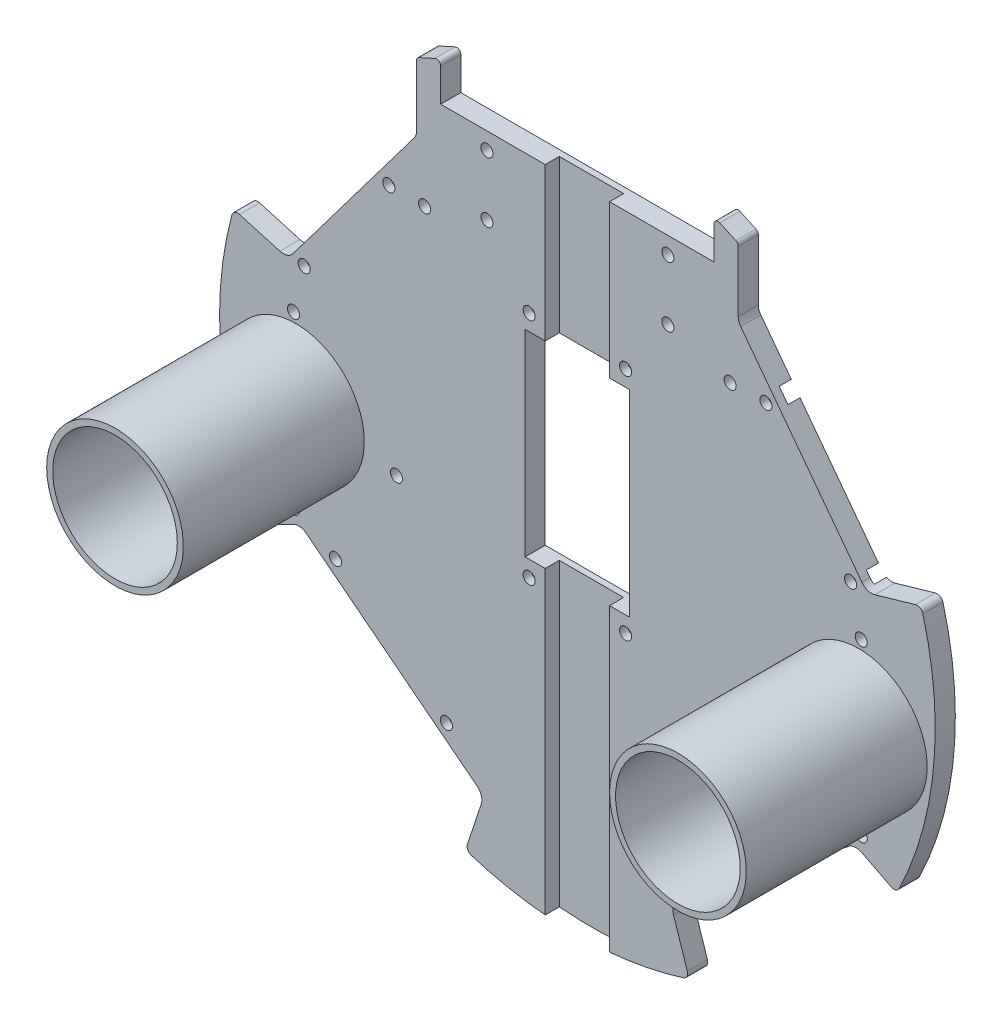
SolidWorks part; units mm, degrees
ref_plane "前视基准面" through (0, 0, 0) normal (0, 0, 1) x (1, 0, 0)
ref_plane "上视基准面" through (0, 0, 0) normal (0, 1, 0) x (1, 0, 0)
ref_plane "右视基准面" through (0, 0, 0) normal (1, 0, 0) x (0, 0, -1)
other "Configuration Table"
sketch "草图1" plane through (0, 0, 0) normal (0, 0, 1) x (1, 0, 0)
  line L0 (0, 70) -> (0, -70) construction
  line L1 (-70, 0) -> (70, 0) construction
  line L2 (40.6041, 62.4314) -> (55.9045, 42.1271)
  line L3 (55.9045, 42.1271) -> (0, 0) construction
  line L4 (55.9045, 42.1271) -> (70.756, 22.4184)
  line L6 (-34, 77) -> (34, 77)
  line L7 (22.5, 65) -> (-22.5, 65) construction
  line L8 (22.5, 65) -> (22.5, 50) construction
  line L9 (22.5, 50) -> (-22.5, 50) construction
  line L10 (-22.5, 65) -> (-22.5, 50) construction
  line L11 (0, 77) -> (0, 70) construction
  line L20 (0, 0) -> (43.0963, -55.1608) construction
  line L22 (43.0963, -55.1608) -> (24.9165, -69.3644)
  line L23 (43.0963, -55.1608) -> (67.4566, -36.1284)
  line L24 (23.9138, -72.6662) -> (27.8213, -84.5398)
  line L25 (70.6599, -35.8166) -> (79.3841, -40.2388)
  line L26 (40, 74) -> (40, 64.2368)
  line L27 (-70.6599, -35.8166) -> (-79.3841, -40.2388)
  line L28 (-43.0963, -55.1608) -> (-67.4566, -36.1284)
  line L29 (-43.0963, -55.1608) -> (-24.9165, -69.3644)
  line L30 (-23.9138, -72.6662) -> (-27.8213, -84.5398)
  line L31 (73.9834, 21.3414) -> (85.5133, 24.6673)
  line L32 (-55.9045, 42.1271) -> (-70.756, 22.4184)
  line L33 (-73.9834, 21.3414) -> (-85.5133, 24.6673)
  line L34 (40, 74) -> (40, 80.064)
  line L35 (34, 77) -> (34, 82.7904)
  line L36 (40, 80.064) -> (34, 82.7904)
  line L37 (-40.6041, 62.4314) -> (-55.9045, 42.1271)
  line L38 (-40, 74) -> (-40, 64.2368)
  line L39 (-40, 74) -> (-40, 80.064)
  line L40 (-40, 80.064) -> (-34, 82.7904)
  line L41 (-34, 77) -> (-34, 82.7904)
  arc A0 (-85.5133, 24.6673) -> (-79.3841, -40.2388) centre (0, 0) ccw
  circle A1 centre (0, 0) radius 70 construction
  circle A5 centre (67.9521, 21.1544) radius 1.5 construction
  circle A6 centre (46.8886, 49.1066) radius 1.5 construction
  circle A17 centre (-67.9521, 21.1544) radius 1.5 construction
  arc A18 (40.6041, 62.4314) -> (40, 64.2368) centre (43, 64.2368) cw
  circle A19 centre (-46.8886, 49.1066) radius 1.5 construction
  circle A21 centre (32.5812, -59.569) radius 1.5 construction
  circle A22 centre (60.1616, -38.0208) radius 1.5 construction
  arc A23 (23.9138, -72.6662) -> (24.9165, -69.3644) centre (26.7635, -71.7284) cw
  arc A24 (70.6599, -35.8166) -> (67.4566, -36.1284) centre (69.3035, -38.4925) ccw
  arc A25 (79.3841, -40.2388) -> (85.5133, 24.6673) centre (0, 0) ccw
  circle A26 centre (-32.5812, -59.569) radius 1.5 construction
  circle A27 centre (-60.1616, -38.0208) radius 1.5 construction
  arc A28 (-70.6599, -35.8166) -> (-67.4566, -36.1284) centre (-69.3035, -38.4925) cw
  arc A29 (-23.9138, -72.6662) -> (-24.9165, -69.3644) centre (-26.7635, -71.7284) ccw
  arc A30 (-27.8213, -84.5398) -> (27.8213, -84.5398) centre (0, 0) ccw
  arc A31 (73.9834, 21.3414) -> (70.756, 22.4184) centre (73.1519, 24.2238) cw
  arc A32 (-73.9834, 21.3414) -> (-70.756, 22.4184) centre (-73.1519, 24.2238) ccw
  circle A33 centre (0, 0) radius 89.5 construction
  arc A34 (-40.6041, 62.4314) -> (-40, 64.2368) centre (-43, 64.2368) ccw
  point P10 (55.9045, 42.1271)
  point P16 (70.581, 24.7855)
  point P21 (0, 65)
  point P33 (40, 63.233)
  point P38 (40, 77)
  point P43 (-40, 63.233)
  point P55 (40, -63.233)
  point P60 (23.2545, -70.6629)
  point P64 (68.9591, -34.9545)
  dimension "D1" = 178
  dimension "D2" = 140
  dimension "D7" = 3
  dimension "D14" = 24
  dimension "D3" = 40
  dimension "D4" = 3
  dimension "D15" = 3
  dimension "D17" = 3
  dimension "D21" = 11
  dimension "D5" = 6
  dimension "D23" = 3
  dimension "D26" = 3
  dimension "D29" = 3
  dimension "D30" = 3
  dimension "D31" = 179
  dimension "D32" = 77
  dimension "D6" = 3
  dimension "D8" = 53
  dimension "D9" = 45
  dimension "D10" = 15
  dimension "D11" = 22.5
  dimension "D12" = 12
  dimension "D13" = 12
  dimension "D16" = 3
  dimension "D18" = 90
  dimension "D19" = 11
  dimension "D20" = 38
  dimension "D22" = 3
  dimension "D24" = 3
  dimension "D25" = 24
  dimension "D27" = 58
  dimension "D28" = 12.5
  dimension "D33" = 6
extrude "整车底板外形拉伸" add sketch "草图1" along normal blind 5
fillet "圆角3" radius 1.5 1 edges at (79.3841, -40.2388, 2.5)
fillet "圆角4" radius 1.5 1 edges at (27.8213, -84.5398, 2.5)
fillet "圆角5" radius 1.5 1 edges at (-27.8213, -84.5398, 2.5)
fillet "圆角6" radius 1.5 1 edges at (-79.3841, -40.2388, 2.5)
fillet "圆角8" radius 1.5 1 edges at (85.5133, 24.6673, 2.5)
fillet "圆角9" radius 1.5 1 edges at (-85.5133, 24.6673, 2.5)
fillet "圆角10" radius 1 4 edges at (-40, 80.064, 2.5) (40, 80.064, 2.5) (-34, 82.7904, 2.5) (34, 82.7904, 2.5)
sketch "草图3" plane through (0, 0, 5) normal (0, 0, 1) x (1, 0, 0)
  circle A0 centre (70, -9.25) radius 17
  dimension "D1" = 34
  dimension "D2" = 9.25
  dimension "D3" = 70
extrude "电容座" add sketch "草图3" along normal blind 45
sketch "草图4" plane through (0, 0, 50) normal (0, 0, 1) x (1, 0, 0)
  circle A0 centre (70, -9.25) radius 15.5
  dimension "D1" = 31
extrude "电容座内部" cut sketch "草图4" against normal blind 45
mirror "镜向1" about plane through (0, 0, 0) normal (1, 0, 0) of "电容座"
mirror "镜向2" about plane through (0, 0, 0) normal (1, 0, 0) of "电容座内部"
sketch "草图5" plane through (0, 0, 5) normal (0, 0, 1) x (1, 0, 0)
  line L0 (70.756, 22.4184) -> (40.6041, 62.4314) construction
  line L1 (0, 0) -> (55.9045, 42.1271) construction
  line L2 (0, 77) -> (0, 0) construction
  line L3 (34, 77) -> (-34, 77) construction
  line L4 (0, 0) -> (43.0963, -55.1608) construction
  line L5 (24.9165, -69.3644) -> (67.4566, -36.1284) construction
  circle A0 centre (46.8886, 49.1066) radius 1.5
  circle A1 centre (67.9521, 21.1544) radius 1.5
  circle A2 centre (-67.9521, 21.1544) radius 1.5
  circle A3 centre (-46.8886, 49.1066) radius 1.5
  circle A4 centre (60.1616, -38.0208) radius 1.5
  circle A5 centre (32.5812, -59.569) radius 1.5
  circle A6 centre (-60.1616, -38.0208) radius 1.5
  circle A7 centre (-32.5812, -59.569) radius 1.5
  dimension "D1" = 3
  dimension "D5" = 24
  dimension "D7" = 3
  dimension "D9" = 3
  dimension "D12" = 3
  dimension "D2" = 3
  dimension "D3" = 11
  dimension "D4" = 53
  dimension "D6" = 3
  dimension "D8" = 142
  dimension "D10" = 24
  dimension "D11" = 3
  dimension "D13" = 11
  dimension "D14" = 3
extrude "电机安装孔上部分" cut sketch "草图5" against normal blind 2
sketch "草图12" plane through (0, 0, 0) normal (0, 0, -1) x (-1, 0, 0)
  line L0 (0, 0) -> (55.9045, 42.1271) construction
  line L1 (40.6041, 62.4314) -> (70.756, 22.4184) construction
  line L2 (0, 0) -> (0, 77) construction
  line L3 (-34, 77) -> (34, 77) construction
  line L4 (0, 0) -> (43.0963, -55.1608) construction
  line L5 (67.4566, -36.1284) -> (24.9165, -69.3644) construction
  circle A0 centre (46.8886, 49.1066) radius 3.5
  circle A1 centre (68.554, 20.3557) radius 3.5
  circle A2 centre (-68.554, 20.3557) radius 3.5
  circle A3 centre (-46.8886, 49.1066) radius 3.5
  circle A4 centre (32.5812, -59.569) radius 3.5
  circle A5 centre (60.1616, -38.0208) radius 3.5
  circle A6 centre (13.527, -115.9287) radius 3.5
  circle A7 centre (-60.1616, -38.0208) radius 3.5
  circle A8 centre (-32.5812, -59.569) radius 3.5
  dimension "D1" = 7
  dimension "D5" = 7
  dimension "D11" = 7
  dimension "D12" = 7
  dimension "D2" = 11
  dimension "D3" = 3
  dimension "D4" = 25
  dimension "D6" = 3
  dimension "D7" = 11
  dimension "D8" = 24
  dimension "D9" = 3
  dimension "D10" = 3
extrude "电机安装孔下部分" cut sketch "草图12" against normal blind 3
sketch "草图7" plane through (0, 0, 5) normal (0, 0, 1) x (1, 0, 0)
  line L0 (-8, 77) -> (-8, -88.6397)
  line L1 (34, 77) -> (-34, 77) construction
  line L2 (-8, 77) -> (8, 77)
  line L4 (0, 0) -> (0, -22.89) construction
  line L5 (8, 77) -> (8, -88.6397)
  arc A1 (-26.3679, -85.0043) -> (26.3679, -85.0043) centre (0, 0) ccw construction
  arc A3 (-8, -88.6397) -> (8, -88.6397) centre (0, 0) ccw
  point P6 (0, -56)
  point P10 (0, 77)
  dimension "D1" = 16
extrude "挑球铲的槽" cut sketch "草图7" against normal blind 3.5
sketch "草图8" plane through (0, 0, 5) normal (0, 0, 1) x (1, 0, 0)
  line L0 (0, 77) -> (0, -5.3656) construction
  line L1 (8, 77) -> (-8, 77) construction
  line L2 (13, 35) -> (-13, 35)
  line L3 (-13, 35) -> (-13, -14)
  line L4 (-13, -14) -> (13, -14)
  line L5 (0, -5.3656) -> (0, -14) construction
  line L6 (-8, 77) -> (-34, 77) construction
  line L7 (13, 35) -> (13, -14)
  point P13 (0, 35)
  dimension "D1" = 49
  dimension "D2" = 13
  dimension "D3" = 42
extrude "安装电磁铁的槽" cut sketch "草图8" against normal blind 5
sketch "草图9" plane through (0, 0, 5) normal (0, 0, 1) x (1, 0, 0)
  line L0 (8, 35) -> (8, 77) construction
  line L1 (13, 35) -> (8, 35) construction
  line L2 (0, 0) -> (0, 32.0784) construction
  line L3 (-13, 10.5) -> (13, 10.5) construction
  line L4 (-13, 35) -> (-13, -14) construction
  line L5 (13, -14) -> (13, 35) construction
  circle A0 centre (12, 39) radius 1.5
  circle A1 centre (-12, 39) radius 1.5
  circle A2 centre (-12, -18) radius 1.5
  circle A3 centre (12, -18) radius 1.5
  dimension "D2" = 3
  dimension "D1" = 4
  dimension "D3" = 4
extrude "安装电磁铁的孔的上半部分" cut sketch "草图9" against normal blind 2
sketch "草图10" plane through (0, 0, 0) normal (0, 0, -1) x (-1, 0, 0)
  line L0 (8, 35) -> (8, 53.2712) construction
  line L1 (-13, 35) -> (13, 35) construction
  line L2 (0, 35) -> (0, 53.2712) construction
  line L3 (-13, 10.5) -> (13, 10.5) construction
  line L4 (-13, -14) -> (-13, 35) construction
  line L5 (13, 35) -> (13, -14) construction
  circle A0 centre (12, 39) radius 3.5
  circle A1 centre (-12, 39) radius 3.5
  circle A2 centre (12, -18) radius 3.5
  circle A3 centre (-12, -18) radius 3.5
  dimension "D4" = 7
  dimension "D1" = 8
  dimension "D2" = 4
  dimension "D3" = 4
extrude "安装电磁铁的孔下半部分" cut sketch "草图10" against normal blind 3
sketch "草图11" plane through (0, 0, 5) normal (0, 0, 1) x (1, 0, 0)
  line L0 (34, 77) -> (8, 77) construction
  line L1 (22.5, 68.8) -> (22.5, 53.8) construction
  line L2 (0, 77) -> (0, 50.9825) construction
  line L3 (8, 77) -> (-8, 77) construction
  circle A0 centre (22.5, 68.8) radius 1.5
  circle A1 centre (22.5, 53.8) radius 1.5
  circle A2 centre (-22.5, 53.8) radius 1.5
  circle A3 centre (-22.5, 68.8) radius 1.5
  dimension "D1" = 3
  dimension "D5" = 3
  dimension "D2" = 8.2
  dimension "D3" = 15
  dimension "D4" = 45
extrude "嘴部安装孔" cut sketch "草图11" against normal blind 5
sketch "草图14" plane through (0, 0, 0) normal (0, 0, -1) x (-1, 0, 0)
  line L0 (34, 77) -> (34, 73)
  line L1 (-34, 77) -> (-34, 73)
  line L2 (-34, 73) -> (34, 73)
  line L3 (-34, 77) -> (34, 77)
extrude "切除-拉伸1" cut sketch "草图14" against normal blind 10
sketch "草图15" plane through (0, 0, 5) normal (0, 0, 1) x (1, 0, 0)
  line L0 (0, 73) -> (0, 23.218) construction
  line L1 (-8, 73) -> (8, 73) construction
  line L2 (-34, 73) -> (-8, 73) construction
  circle A2 centre (-45, -12.5) radius 1.5
  circle A3 centre (-38, 49) radius 1.5
  circle A4 centre (38, 49) radius 1.5
  circle A5 centre (45, -12.5) radius 1.5
  dimension "D1" = 3
  dimension "D2" = 76
  dimension "D3" = 24
  dimension "D5" = 3
  dimension "D4" = 61.5
  dimension "D6" = 90
extrude "电池盒安装孔" cut sketch "草图15" against normal through all
sketch "草图16" plane through (0, 0, 5) normal (0, 0, 1) x (1, 0, 0)
  line L13 (-70.6, 10) -> (70.6, 10) construction
  line L14 (-70.6, 10) -> (-70.6, -32.2) construction
  line L15 (-70.6, -32.2) -> (70.6, -32.2) construction
  line L16 (70.6, 10) -> (70.6, -32.2) construction
  line L17 (-8, 73) -> (8, 73) construction
  circle A0 centre (-70.6, -32.2) radius 1.5
  circle A1 centre (-70.6, 10) radius 1.5
  circle A2 centre (70.6, 10) radius 1.5
  circle A3 centre (70.6, -32.2) radius 1.5
  point P1 (0, 0)
  dimension "D5" = 3
  dimension "D6" = 3
  dimension "D7" = 3
  dimension "D8" = 3
  dimension "D1" = 141.2
  dimension "D2" = 42.2
  dimension "D3" = 63
  dimension "D4" = 70.6
extrude "电路板安装孔" cut sketch "草图16" against normal blind 10
